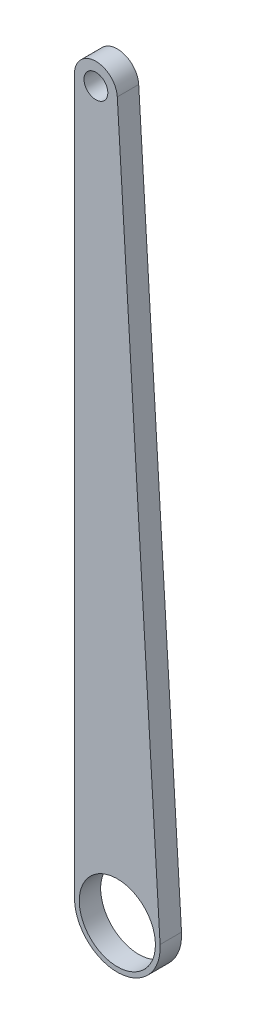
SolidWorks part; units mm, degrees
ref_plane "정면" through (0, 0, 0) normal (0, 0, 1) x (1, 0, 0)
ref_plane "윗면" through (0, 0, 0) normal (0, 1, 0) x (1, 0, 0)
ref_plane "우측면" through (0, 0, 0) normal (1, 0, 0) x (0, 0, -1)
sketch "스케치1" plane through (0, 0, 0) normal (0, 0, 1) x (1, 0, 0)
  line L0 (-9, 0) -> (-9, 150)
  line L1 (8.9838, 0.5395) -> (-0.0081, 150.2698)
  circle A0 centre (0, 0) radius 8
  circle A1 centre (0, 0) radius 9
  arc A2 (-9, 150) -> (-0.0081, 150.2698) centre (-4.5, 150) cw
  circle A3 centre (-4.5, 150) radius 2.5
  dimension "D1" = 16
  dimension "D2" = 18
  dimension "D3" = 4.5
  dimension "D5" = 5
  dimension "D4" = 150
extrude "보스-돌출1" add sketch "스케치1" along normal blind 4.5 contours A2 L0 A1 L1 A3 | A0
